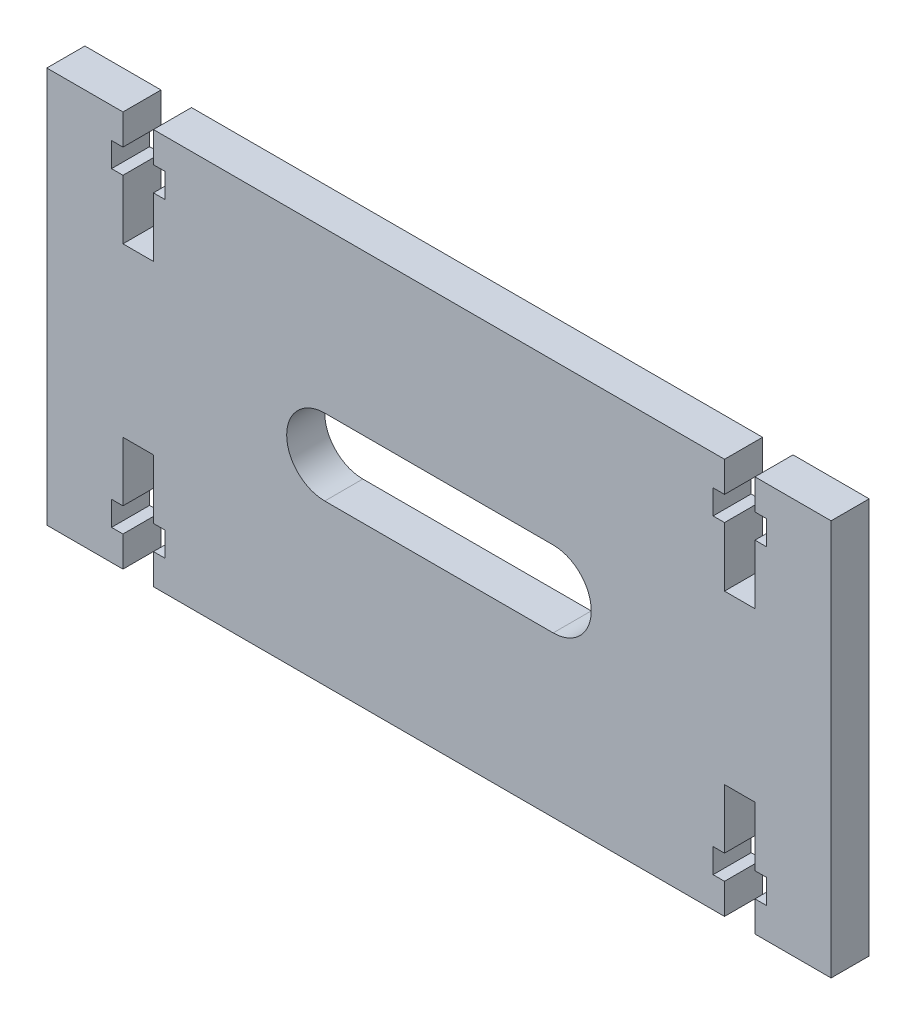
SolidWorks part; units mm, degrees
ref_plane "Front Plane" through (0, 0, 0) normal (0, 0, 1) x (1, 0, 0)
ref_plane "Top Plane" through (0, 0, 0) normal (0, 1, 0) x (1, 0, 0)
ref_plane "Right Plane" through (0, 0, 0) normal (1, 0, 0) x (0, 0, -1)
sketch "Sketch1" plane through (0, 0, 0) normal (0, 0, 1) x (1, 0, 0)
  line L1 (-51.5, 26) -> (51.5, 26)
  line L2 (-51.5, 26) -> (-51.5, -26)
  line L3 (-51.5, -26) -> (51.5, -26)
  line L4 (51.5, 26) -> (51.5, -26)
  dimension "D1" = 52
  dimension "D2" = 103
  dimension "D3" = 51.5
  dimension "D4" = 26
extrude "Boss-Extrude1" add sketch "Sketch1" along normal blind 5
sketch "Sketch2" plane through (0, 0, 5) normal (0, 0, 1) x (1, 0, 0)
  line L0 (41.5, -26) -> (41.5, -22)
  line L1 (-51.5, -26) -> (51.5, -26) construction
  line L2 (41.5, -22) -> (43, -22)
  line L3 (43, -22) -> (43, -18.8)
  line L4 (43, -18.8) -> (41.5, -18.8)
  line L5 (41.5, -18.8) -> (41.5, -11)
  line L6 (41.5, -11) -> (37.5, -11)
  line L7 (37.5, -11) -> (37.5, -18.8)
  line L8 (37.5, -18.8) -> (36, -18.8)
  line L9 (36, -18.8) -> (36, -22)
  line L10 (36, -22) -> (37.5, -22)
  line L11 (37.5, -22) -> (37.5, -26)
  line L12 (37.5, -26) -> (41.5, -26)
  line L13 (51.5, -26) -> (51.5, 26) construction
  line L14 (0, 0) -> (0, -26.8446) construction
  line L15 (0, 0) -> (60.7612, 0) construction
  line L16 (37.5, 26) -> (41.5, 26)
  line L17 (37.5, 22) -> (37.5, 26)
  line L18 (36, 22) -> (37.5, 22)
  line L19 (36, 18.8) -> (36, 22)
  line L20 (37.5, 18.8) -> (36, 18.8)
  line L21 (37.5, 11) -> (37.5, 18.8)
  line L22 (41.5, 11) -> (37.5, 11)
  line L23 (41.5, 18.8) -> (41.5, 11)
  line L24 (43, 18.8) -> (41.5, 18.8)
  line L25 (43, 22) -> (43, 18.8)
  line L26 (41.5, 22) -> (43, 22)
  line L27 (41.5, 26) -> (41.5, 22)
  line L28 (-37.5, -26) -> (-41.5, -26)
  line L29 (-37.5, -22) -> (-37.5, -26)
  line L30 (-36, -22) -> (-37.5, -22)
  line L31 (-36, -18.8) -> (-36, -22)
  line L32 (-37.5, -18.8) -> (-36, -18.8)
  line L33 (-37.5, -11) -> (-37.5, -18.8)
  line L34 (-41.5, -11) -> (-37.5, -11)
  line L35 (-41.5, -18.8) -> (-41.5, -11)
  line L36 (-43, -18.8) -> (-41.5, -18.8)
  line L37 (-43, -22) -> (-43, -18.8)
  line L38 (-41.5, -22) -> (-43, -22)
  line L39 (-41.5, -26) -> (-41.5, -22)
  line L40 (-41.5, 26) -> (-41.5, 22)
  line L41 (-41.5, 22) -> (-43, 22)
  line L42 (-43, 22) -> (-43, 18.8)
  line L43 (-43, 18.8) -> (-41.5, 18.8)
  line L44 (-41.5, 18.8) -> (-41.5, 11)
  line L45 (-41.5, 11) -> (-37.5, 11)
  line L46 (-37.5, 11) -> (-37.5, 18.8)
  line L47 (-37.5, 18.8) -> (-36, 18.8)
  line L48 (-36, 18.8) -> (-36, 22)
  line L49 (-36, 22) -> (-37.5, 22)
  line L50 (-37.5, 22) -> (-37.5, 26)
  line L51 (-37.5, 26) -> (-41.5, 26)
  dimension "D1" = 4
  dimension "D2" = 1.5
  dimension "D3" = 1.5
  dimension "D4" = 15
  dimension "D5" = 4
  dimension "D6" = 3.2
  dimension "D7" = 10
extrude "Cut-Extrude1" cut sketch "Sketch2" against normal blind 10
sketch "Sketch3" plane through (0, 0, 0) normal (0, 0, -1) x (-1, 0, 0)
  line L0 (-15, 0) -> (15, 0) construction
  line L1 (-15, 5) -> (15, 5)
  line L2 (-15, -5) -> (15, -5)
  arc A0 (-15, 5) -> (-15, -5) centre (-15, 0) ccw
  arc A1 (15, -5) -> (15, 5) centre (15, 0) ccw
  point P3 (0, 0)
  dimension "D1" = 10
  dimension "D2" = 30
extrude "Cut-Extrude2" cut sketch "Sketch3" against normal blind 10
